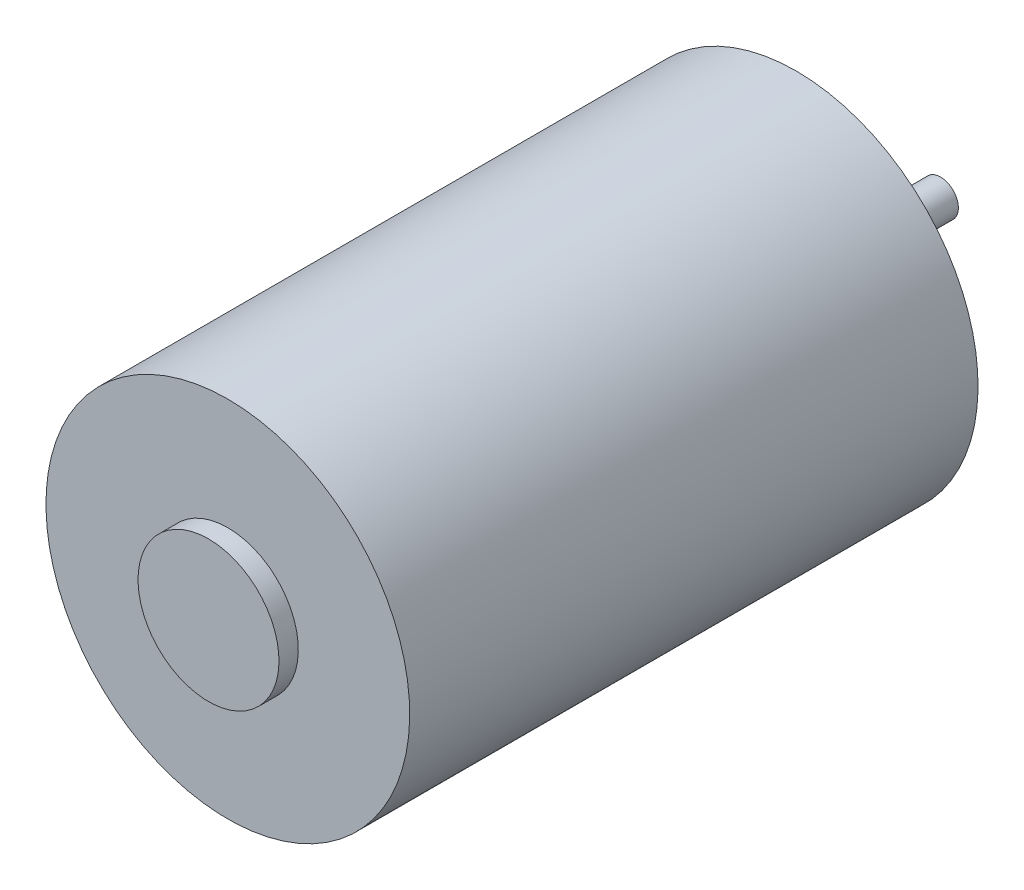
SolidWorks part; units mm, degrees
ref_plane "Front Plane" through (0, 0, 0) normal (0, 0, 1) x (1, 0, 0)
ref_plane "Top Plane" through (0, 0, 0) normal (0, 1, 0) x (1, 0, 0)
ref_plane "Right Plane" through (0, 0, 0) normal (1, 0, 0) x (0, 0, -1)
sketch "Sketch2" plane through (0, 0, 0) normal (1, 0, 0) x (0, 0, -1)
  line L0 (0, 0) -> (0, -6.2)
  line L1 (1.7, -16) -> (51.7, -16)
  line L2 (53.4, -1.57) -> (53.4, -6.2)
  line L3 (53.4, -1.57) -> (64.4, -1.57)
  line L4 (64.4, -1.57) -> (64.4, 0)
  line L5 (64.4, 0) -> (0, 0)
  line L6 (53.4, -6.2) -> (51.7, -6.2)
  line L7 (51.7, -6.2) -> (51.7, -16)
  line L8 (0, -6.2) -> (1.7, -6.2)
  line L9 (1.7, -6.2) -> (1.7, -16)
  dimension "D1" = 1.57
  dimension "D2" = 11
  dimension "D3" = 6.2
  dimension "D4" = 1.7
  dimension "D5" = 16
  dimension "D6" = 50
revolve "Revolve1" add sketch "Sketch2" angle 360 about L5
sketch "Sketch3" plane through (0, 0, -51.7) normal (0, 0, -1) x (-1, 0, 0)
  line L0 (12.7, 0) -> (0, 0) construction
  line L1 (0, 0) -> (-12.7, 0) construction
  circle A0 centre (12.7, 0) radius 2
  circle A1 centre (-12.7, 0) radius 2
  dimension "D1" = 4
  dimension "D2" = 25.4
extrude "Extrude1" cut sketch "Sketch3" against normal blind 10
